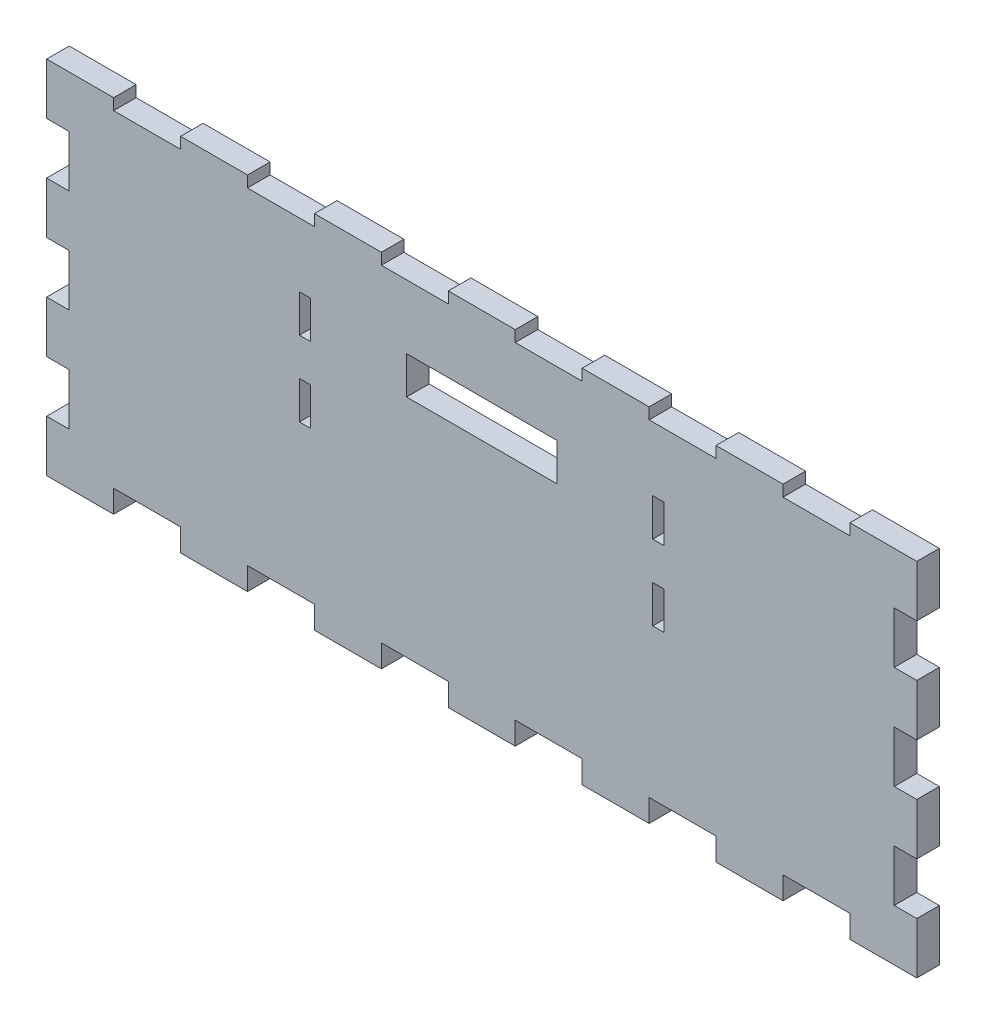
SolidWorks part; units mm, degrees
material "Balsa"
ref_plane "Front" through (0, 0, 0) normal (0, 0, 1) x (1, 0, 0)
ref_plane "Top" through (0, 0, 0) normal (0, 1, 0) x (1, 0, 0)
ref_plane "Right" through (0, 0, 0) normal (1, 0, 0) x (0, 0, -1)
sketch "Esboço1" plane through (0, 0, 0) normal (0, 0, 1) x (1, 0, 0)
  line L1 (115.75, -48) -> (-115.75, -48)
  line L2 (115.75, -48) -> (115.75, 48)
  line L3 (115.75, 48) -> (-115.75, 48)
  line L4 (-115.75, -48) -> (-115.75, 48)
  line L5 (115.75, -48) -> (-115.75, 48) construction
  line L6 (115.75, 48) -> (-115.75, -48) construction
  point P0 (0, 0)
  dimension "D1" = 231.5
  dimension "D2" = 96
extrude "Ressalto-extrusão1" add sketch "Esboço1" along normal blind 6
sketch "Esboço2" plane through (0, 0, 0) normal (0, 0, -1) x (-1, 0, 0)
  line L0 (26.7023, -42) -> (8.89, -42)
  line L1 (62.3223, -42) -> (44.51, -42)
  line L2 (62.3223, -48) -> (44.51, -48)
  line L3 (26.7023, -48) -> (8.89, -48)
  line L4 (97.9423, -48) -> (97.9423, -42)
  line L5 (80.13, -48) -> (80.13, -42)
  line L6 (-8.9177, -42) -> (-26.73, -42)
  line L7 (62.3223, -48) -> (62.3223, -42)
  line L8 (-8.9177, -48) -> (-26.73, -48)
  line L9 (44.51, -48) -> (44.51, -42)
  line L10 (-44.5377, -42) -> (-62.35, -42)
  line L11 (26.7023, -48) -> (26.7023, -42)
  line L12 (-44.5377, -48) -> (-62.35, -48)
  line L13 (8.89, -48) -> (8.89, -42)
  line L14 (-80.1577, -42) -> (-97.97, -42)
  line L15 (-8.9177, -48) -> (-8.9177, -42)
  line L16 (-80.1577, -48) -> (-97.97, -48)
  line L17 (-26.73, -48) -> (-26.73, -42)
  line L18 (-80.1577, 51) -> (-97.97, 51)
  line L19 (-44.5377, -48) -> (-44.5377, -42)
  line L20 (-62.35, 45) -> (-44.5377, 45)
  line L21 (-62.35, -48) -> (-62.35, -42)
  line L22 (-44.5377, 51) -> (-62.35, 51)
  line L23 (-80.1577, -48) -> (-80.1577, -42)
  line L24 (-26.73, 45) -> (-8.9177, 45)
  line L25 (-97.97, -48) -> (-97.97, -42)
  line L26 (-8.9177, 51) -> (-26.73, 51)
  line L27 (8.89, 45) -> (26.7023, 45)
  line L29 (80.13, 45) -> (80.13, 51)
  line L31 (62.3223, 45) -> (62.3223, 51)
  line L32 (62.3223, 51) -> (44.51, 51)
  line L33 (44.51, 45) -> (44.51, 51)
  line L34 (80.13, 45) -> (97.9423, 45)
  line L35 (26.7023, 45) -> (26.7023, 51)
  line L36 (26.7023, 51) -> (8.89, 51)
  line L37 (8.89, 45) -> (8.89, 51)
  line L38 (44.51, 45) -> (62.3223, 45)
  line L39 (-8.9177, 45) -> (-8.9177, 51)
  line L41 (-26.73, 45) -> (-26.73, 51)
  line L43 (-44.5377, 45) -> (-44.5377, 51)
  line L45 (-62.35, 45) -> (-62.35, 51)
  line L47 (-80.1577, 45) -> (-80.1577, 51)
  line L49 (-97.97, 45) -> (-97.97, 51)
  line L55 (97.9423, 45) -> (97.9423, 51)
  line L56 (97.9423, -42) -> (80.13, -42)
  line L57 (97.9423, -48) -> (80.13, -48)
  line L58 (97.9423, 51) -> (80.13, 51)
  line L59 (-97.97, 45) -> (-80.1577, 45)
  line L61 (-115.7777, -48) -> (-115.7777, -42) [skipped]
  line L62 (-115.7777, 45) -> (-115.7777, 51) [skipped]
  dimension "D1" = 6
  dimension "D3" = 7
  dimension "D4" = 2
extrude "Corte-extrusão1" cut sketch "Esboço2" against normal up to next
sketch "Esboço3" plane through (0, 0, 0) normal (0, 0, 1) x (1, 0, 0)
  line L1 (115.75, -48) -> (-115.75, -48)
  line L2 (115.75, -48) -> (115.75, 48)
  line L3 (115.75, 48) -> (-115.75, 48)
  line L4 (-115.75, -48) -> (-115.75, 48)
  line L5 (115.75, -48) -> (-115.75, 48) construction
  line L6 (115.75, 48) -> (-115.75, -48) construction
  point P0 (0, 0)
  dimension "D1" = 231.5
  dimension "D2" = 96
sketch "Esboço4" plane through (0, 0, 0) normal (0, 0, -1) x (-1, 0, 0)
  line L0 (109.75, -6.86) -> (109.75, 6.8557)
  line L3 (115.75, 34.2857) -> (109.75, 34.2857)
  line L5 (115.75, -6.86) -> (115.75, 6.8557)
  line L6 (-109.75, 34.2857) -> (-115.75, 34.2857)
  line L7 (109.75, 20.57) -> (109.75, 34.2857)
  line L8 (-109.75, 20.57) -> (-115.75, 20.57)
  line L9 (115.75, 20.57) -> (115.75, 34.2857)
  line L10 (-109.75, 6.8557) -> (-115.75, 6.8557)
  line L12 (-109.75, -6.86) -> (-115.75, -6.86)
  line L13 (-115.75, 20.57) -> (-115.75, 34.2857)
  line L14 (-109.75, -20.5743) -> (-115.75, -20.5743)
  line L15 (-109.75, 20.57) -> (-109.75, 34.2857)
  line L16 (-109.75, -34.29) -> (-115.75, -34.29)
  line L17 (-115.75, -6.86) -> (-115.75, 6.8557)
  line L18 (-109.75, -6.86) -> (-109.75, 6.8557)
  line L20 (115.75, 20.57) -> (109.75, 20.57)
  line L22 (115.75, 6.8557) -> (109.75, 6.8557)
  line L24 (115.75, -6.86) -> (109.75, -6.86)
  line L26 (115.75, -20.5743) -> (109.75, -20.5743)
  line L28 (115.75, -34.29) -> (109.75, -34.29)
  line L32 (115.75, -34.29) -> (115.75, -20.5743)
  line L33 (109.75, -34.29) -> (109.75, -20.5743)
  line L34 (-109.75, -34.29) -> (-109.75, -20.5743)
  line L35 (-115.75, -34.29) -> (-115.75, -20.5743)
  line L37 (-109.75, -48.0043) -> (-115.75, -48.0043) [skipped]
  line L49 (115.75, -48.0043) -> (109.75, -48.0043) [skipped]
  dimension "D1" = 6
  dimension "D3" = 2
  dimension "D4" = 4
extrude "Corte-extrusão3" cut sketch "Esboço4" against normal up to next
sketch "Esboço5" plane through (0, 0, 0) normal (0, 0, -1) x (-1, 0, 0)
  line L0 (0, 48) -> (0, 28) construction
  line L1 (-115.75, 48) -> (115.75, 48) construction
  line L2 (0, 28) -> (0, 23) construction
  line L4 (-20, 28) -> (20, 28)
  line L5 (-20, 28) -> (-20, 18)
  line L6 (-20, 18) -> (20, 18)
  line L7 (20, 28) -> (20, 18)
  line L8 (-20, 28) -> (20, 18) construction
  line L9 (-20, 18) -> (20, 28) construction
  dimension "D1" = 20
  dimension "D2" = 40
  dimension "D3" = 10
extrude "Corte-extrusão4" cut sketch "Esboço5" against normal up to next
sketch "Esboço6" plane through (0, 0, 0) normal (0, 0, -1) x (-1, 0, 0)
  line L3 (48.5, 28) -> (48.5, 18)
  line L14 (-45.5, 28) -> (-48.5, 28)
  line L15 (-45.5, 28) -> (-45.5, 18)
  line L16 (-45.5, 18) -> (-48.5, 18)
  line L17 (-48.5, 28) -> (-48.5, 18)
  line L18 (-45.5, 8) -> (-48.5, 8)
  line L19 (-45.5, 8) -> (-45.5, -2)
  line L20 (-45.5, -2) -> (-48.5, -2)
  line L21 (-48.5, 8) -> (-48.5, -2)
  line L22 (48.5, 28) -> (45.5, 28)
  line L24 (48.5, 18) -> (45.5, 18)
  line L25 (45.5, 28) -> (45.5, 18)
  line L26 (48.5, 8) -> (45.5, 8)
  line L27 (48.5, 8) -> (48.5, -2)
  line L28 (48.5, -2) -> (45.5, -2)
  line L29 (45.5, 8) -> (45.5, -2)
extrude "Corte-extrusão5" cut sketch "Esboço6" against normal up to next
